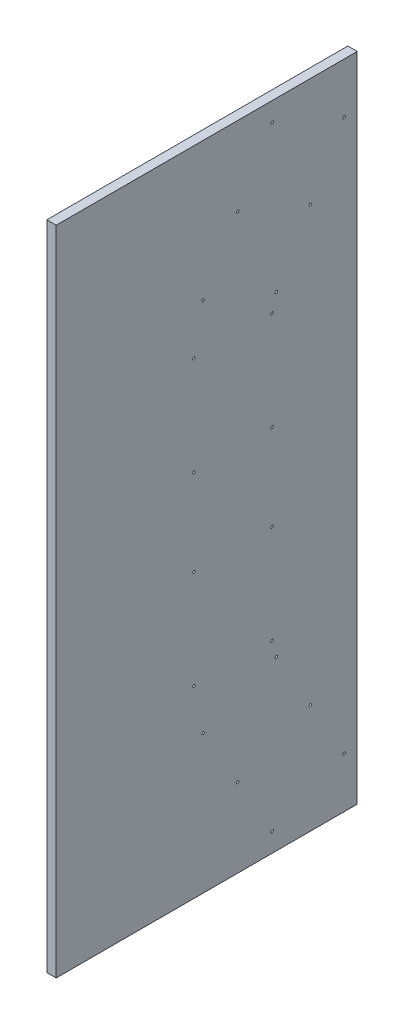
SolidWorks part; units mm, degrees
material "Pine"
ref_plane "Front Plane" through (0, 0, 0) normal (1, 0, 0) x (0, 1, 0)
ref_plane "Top Plane" through (0, 0, 0) normal (0, 0, 1) x (0, 1, 0)
ref_plane "Right Plane" through (0, 0, 0) normal (0, 1, 0) x (-1, 0, 0)
sketch "Sketch2" plane through (0, 0, 0) normal (1, 0, 0) x (0, 1, 0)
  line L2 (-659.75, 305.1657) -> (661.25, 305.1657)
  line L3 (-659.75, 305.1657) -> (-659.75, -304.8343)
  line L4 (-659.75, -304.8343) -> (661.25, -304.8343)
  line L5 (661.25, 305.1657) -> (661.25, -304.8343)
  line L6 (-659.75, 305.1657) -> (661.25, -304.8343) construction
  line L7 (-659.75, -304.8343) -> (661.25, 305.1657) construction
  circle A20 centre (558.7777, -278.265) radius 2.5
  circle A21 centre (439.8724, -209.615) radius 2.5
  circle A22 centre (320.9671, -140.965) radius 2.5
  circle A23 centre (622.9507, -132.514) radius 2.5
  circle A24 centre (501.7072, -62.514) radius 2.5
  circle A25 centre (380.4636, 7.486) radius 2.5
  circle A26 centre (288.05, 26.1657) radius 2.5
  circle A27 centre (288.05, -132.1449) radius 2.5
  circle A28 centre (88.05, -132.1449) radius 2.5
  circle A29 centre (88.05, 26.1657) radius 2.5
  circle A30 centre (-86.55, -132.1449) radius 2.5
  circle A31 centre (-86.55, 26.1657) radius 2.5
  circle A32 centre (-286.55, 26.1657) radius 2.5
  circle A33 centre (-286.55, -132.1449) radius 2.5
  circle A34 centre (-557.2777, -278.265) radius 2.5
  circle A35 centre (-438.3724, -209.615) radius 2.5
  circle A36 centre (-319.4671, -140.965) radius 2.5
  circle A37 centre (-378.9636, 7.486) radius 2.5
  circle A38 centre (-500.2072, -62.514) radius 2.5
  circle A39 centre (-621.4507, -132.514) radius 2.5
  point P2 (0.75, 0.1657)
  point P7 (0, 0)
  point P10 (0, 0)
  point P73 (0, 0)
  dimension "D2" = 1321
  dimension "D3" = 610
extrude "Boss-Extrude1" add sketch "Sketch2" along normal blind 19.05
